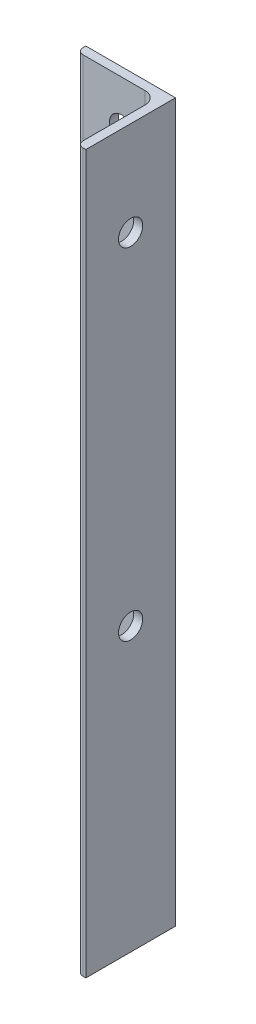
SolidWorks part; units mm, degrees
ref_plane "Front Plane" through (0, 0, 0) normal (0, 0, 1) x (1, 0, 0)
ref_plane "Top Plane" through (0, 0, 0) normal (0, 1, 0) x (1, 0, 0)
ref_plane "Right Plane" through (0, 0, 0) normal (1, 0, 0) x (0, 0, -1)
sketch "Sketch1" plane through (0, 0, 0) normal (0, 1, 0) x (1, 0, 0)
  line L6 (0, 0) -> (-50, 0)
  line L10 (0, 0) -> (0, -50)
  line L11 (0, -50) -> (-1.5, -50)
  line L12 (-50, 0) -> (-50, -1.5)
  line L15 (-46.5, -5) -> (-12, -5)
  line L16 (-5, -46.5) -> (-5, -12)
  arc A8 (-12, -5) -> (-5, -12) centre (-12, -12) cw
  arc A9 (-1.5, -50) -> (-5, -46.5) centre (-1.5, -46.5) cw
  arc A10 (-50, -1.5) -> (-46.5, -5) centre (-46.5, -1.5) ccw
  point P1 (0, 0)
  dimension "D4" = 5
  dimension "D5" = 7
  dimension "D6" = 3.5
  dimension "D1" = 50
  dimension "D2" = 50
  dimension "D3" = 5
extrude "Boss-Extrude1" add sketch "Sketch1" along normal mid plane 400
sketch "Sketch2" plane through (0, 0, 0) normal (0, 0, -1) x (-1, 0, 0)
  line L0 (0, 200) -> (0, -200) construction
  line L1 (0, 200) -> (50, 200) construction
  circle A0 centre (25, 175) radius 6.75
  circle A1 centre (25, 0) radius 6.75
  dimension "D1" = 13.5
  dimension "D2" = 25
  dimension "D3" = 25
  dimension "D4" = 175
extrude "Cut-Extrude1" cut sketch "Sketch2" against normal up to next
sketch "Sketch3" plane through (0, 0, 0) normal (1, 0, 0) x (0, 0, -1)
  line L0 (0, 27.5) -> (0, -27.5) construction
  line L1 (-12, 200) -> (-46.5, 200) construction
  circle A0 centre (-25, 147.5) radius 6.75
  circle A1 centre (-25, -42.5) radius 6.75
  point P8 (0, 0)
  dimension "D1" = 190
  dimension "D3" = 13.5
  dimension "D2" = 25
  dimension "D4" = 52.5
extrude "Cut-Extrude2" cut sketch "Sketch3" against normal up to next
